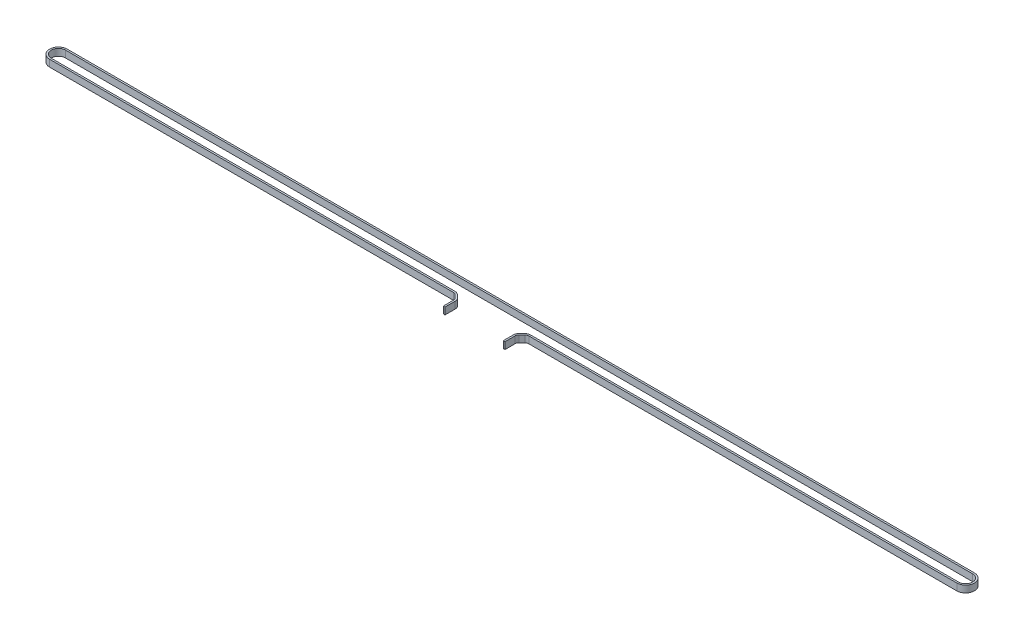
SolidWorks part; units mm, degrees
material "Rubber"
ref_plane "Front Plane" through (0, 0, 0) normal (0, 0, 1) x (1, 0, 0)
ref_plane "Top Plane" through (0, 0, 0) normal (0, 1, 0) x (1, 0, 0)
ref_plane "Right Plane" through (0, 0, 0) normal (1, 0, 0) x (0, 0, -1)
sketch "Sketch1" plane through (0, 0, 0) normal (0, 1, 0) x (1, 0, 0)
  line L0 (397, 0) -> (-397, 0) construction
  line L1 (397, -7.7) -> (-397, -7.7)
  line L2 (397, 7.7) -> (-397, 7.7)
  line L3 (397, -6.2) -> (-397, -6.2)
  line L4 (397, 6.2) -> (-397, 6.2)
  arc A2 (397, -7.7) -> (397, 7.7) centre (397, 0) ccw
  arc A3 (-397, 7.7) -> (-397, -7.7) centre (-397, 0) ccw
  arc A4 (-397, 6.2) -> (-397, -6.2) centre (-397, 0) ccw
  arc A5 (397, -6.2) -> (397, 6.2) centre (397, 0) ccw
  point P2 (0, 0)
  dimension "D1" = 794
  dimension "D2" = 15.4
  dimension "D3" = 1.5
extrude "Boss-Extrude1" add sketch "Sketch1" along normal mid plane 6
sketch "Sketch2" plane through (0, 0, 0) normal (0, 1, 0) x (1, 0, 0)
  line L0 (-36.1458, -11.5) -> (-36.1458, -14.5) construction
  line L1 (-36.1458, -11.5) -> (-36.1458, -14.5)
  line L2 (14.8542, -14.5) -> (14.8542, -11.5) construction
  line L3 (14.8542, -14.5) -> (14.8542, -11.5)
  line L4 (-36.1458, -11.5) -> (-41.6458, -6.2)
  line L5 (-397, -6.2) -> (397, -6.2) construction
  line L6 (-36.1458, -14.5) -> (-36.1458, -22.5)
  line L7 (-36.1458, -22.5) -> (-37.6458, -22.5)
  line L8 (-37.6458, -22.5) -> (-37.6458, -12.1377)
  line L9 (-37.6458, -12.1377) -> (-43.8075, -6.2)
  line L10 (-43.8075, -6.2) -> (-41.6458, -6.2)
  line L11 (14.8542, -11.5) -> (20.3542, -6.2)
  line L12 (20.3542, -6.2) -> (22.5159, -6.2)
  line L13 (22.5159, -6.2) -> (16.3542, -12.1377)
  line L14 (16.3542, -12.1377) -> (16.3542, -22.5)
  line L15 (16.3542, -22.5) -> (14.8542, -22.5)
  line L16 (14.8542, -22.5) -> (14.8542, -14.5)
  dimension "D1" = 5.5
  dimension "D2" = 5.5
  dimension "D3" = 1.5
  dimension "D4" = 1.5
  dimension "D5" = 1.5
  dimension "D6" = 8
extrude "Boss-Extrude2" add sketch "Sketch2" along normal mid plane 6
sketch "Sketch3" plane through (0, 3, 0) normal (0, 1, 0) x (1, 0, 0)
  line L0 (-40.0892, -7.7) -> (-41.6458, -6.2)
  line L1 (-397, -6.2) -> (397, -6.2) construction
  line L2 (-41.6458, -6.2) -> (20.3542, -6.2)
  line L3 (20.3542, -6.2) -> (18.7976, -7.7)
  line L4 (18.7976, -7.7) -> (-40.0892, -7.7)
  line L5 (-36.1458, -11.5) -> (-40.0892, -7.7) construction
  line L6 (18.7976, -7.7) -> (14.8542, -11.5) construction
extrude "Cut-Extrude1" cut sketch "Sketch3" against normal through all
fillet "Fillet1" radius 5 4 edges at (20.3542, 0, 6.2) (14.8542, 0, 11.5) (-36.1458, 0, 11.5) (-41.6458, 0, 6.2)
fillet "Fillet2" radius 3.5 4 edges at (20.9593, 0, 7.7) (16.3542, 0, 12.1377) (-37.6458, 0, 12.1377) (-42.2509, 0, 7.7)
